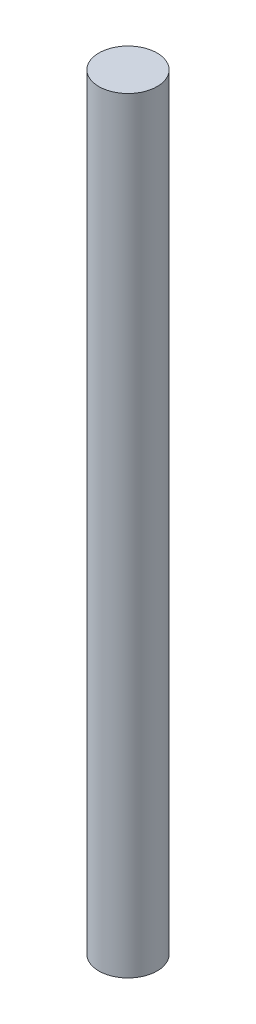
SolidWorks part; units mm, degrees
material "ABS PC"
ref_plane "Front Plane" through (0, 0, 0) normal (0, 0, 1) x (1, 0, 0)
ref_plane "Top Plane" through (0, 0, 0) normal (0, 1, 0) x (1, 0, 0)
ref_plane "Right Plane" through (0, 0, 0) normal (1, 0, 0) x (0, 0, -1)
sketch "Sketch1" plane through (0, 0, 0) normal (0, 1, 0) x (1, 0, 0)
  circle A0 centre (0, 0) radius 0.95
  dimension "D1" = 1.9
extrude "Boss-Extrude1" add sketch "Sketch1" along normal blind 25
